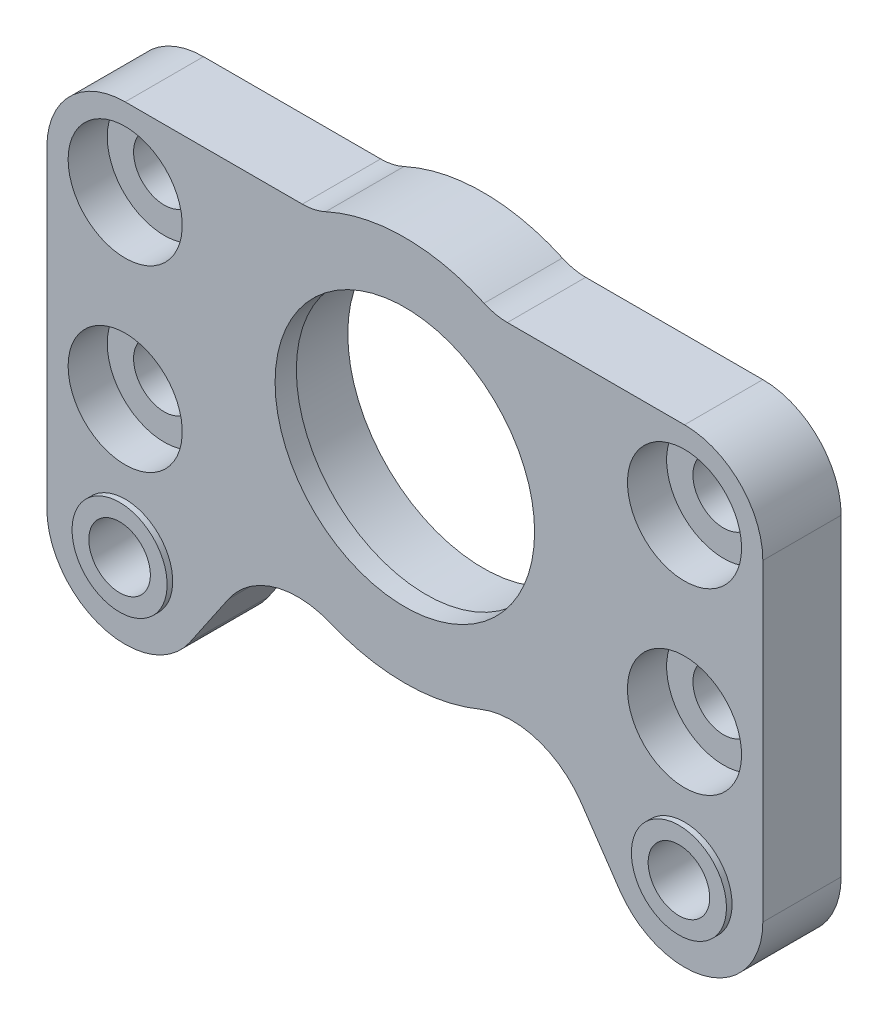
SolidWorks part; units mm, degrees
ref_plane "Front Plane" through (0, 0, 0) normal (0, 0, 1) x (1, 0, 0)
ref_plane "Top Plane" through (0, 0, 0) normal (0, 1, 0) x (1, 0, 0)
ref_plane "Right Plane" through (0, 0, 0) normal (1, 0, 0) x (0, 0, -1)
sketch "Sketch1" plane through (0, 0, 0) normal (0, 0, 1) x (1, 0, 0)
  line L4 (64, 35) -> (64, 7)
  line L7 (32, 27) -> (20.4, 27) construction
  line L8 (51.2137, 3.0607) -> (47.7667, 8.1237)
  line L10 (32, 44) -> (32, 38.6)
  line L11 (40, 42) -> (57, 42)
  line L12 (32, 15.4) -> (32, 9.5)
  line L13 (32, 38.6) -> (32, 15.4) construction
  line L14 (57, 35) -> (57, 7) construction
  arc A0 (32, 15.4) -> (32, 38.6) centre (32, 27) ccw
  arc A1 (40, 42) -> (32, 44) centre (32, 27) ccw
  arc A2 (32, 9.5) -> (38.697, 10.8321) centre (32, 27) ccw
  arc A3 (51.2137, 3.0607) -> (64, 7) centre (57, 7) ccw
  arc A4 (47.7667, 8.1237) -> (38.697, 10.8321) centre (41.5671, 3.903) ccw
  arc A5 (57, 42) -> (64, 35) centre (57, 35) cw
  dimension "D1" = 7
  dimension "D4" = 11.6
  dimension "D5" = 17
  dimension "D6" = 17.5
  dimension "D7" = 7.5
  dimension "D8" = 20
  dimension "D2" = 28
  dimension "D3" = 25
  dimension "D9" = 15
extrude "Boss-Extrude1" add sketch "Sketch1" along normal blind 7 separate body
sketch "Sketch3" plane through (0, 0, 7) normal (0, 0, 1) x (1, 0, 0)
  line L0 (57, 35) -> (57, 19) construction
  line L1 (57, 19) -> (57, 7) construction
  circle A0 centre (57, 35) radius 2.75
  circle A1 centre (57, 19) radius 2.75
  circle A2 centre (57, 7) radius 2.75
  dimension "D1" = 5.5
  dimension "D2" = 16
  dimension "D3" = 12
extrude "Cut-Extrude1" cut sketch "Sketch3" against normal through all both and the other way through all
sketch "Sketch4" plane through (0, 0, 0) normal (0, 0, -1) x (-1, 0, 0)
  circle A0 centre (-32, 27) radius 12.1
  dimension "D1" = 24.2
extrude "Cut-Extrude2" cut sketch "Sketch4" against normal blind 5.1
sketch "Sketch5" plane through (0, 0, 7) normal (0, 0, 1) x (1, 0, 0)
  circle A0 centre (57, 7) radius 2.75 construction
  circle A1 centre (57, 7) radius 2.75
  circle A2 centre (57, 7) radius 4.25
  dimension "D1" = 8.5
extrude "Boss-Extrude2" add sketch "Sketch5" along normal blind 0.5
sketch "Sketch6" plane through (0, 0, 7) normal (0, 0, 1) x (1, 0, 0)
  circle A0 centre (57, 19) radius 5.1
  circle A1 centre (57, 35) radius 5.1
  dimension "D1" = 10.2
extrude "Cut-Extrude3" cut sketch "Sketch6" against normal blind 3.5
fillet "Fillet1" radius 5 1 edges at (40, 42, 3.5)
sketch "Sketch8" plane through (0, 0, 0) normal (0, 0, -1) x (-1, 0, 0)
  line L1 (-54.5463, 11.25) -> (-59.4537, 11.25)
  line L2 (-59.4537, 11.25) -> (-61.9075, 7)
  line L3 (-61.9075, 7) -> (-59.4537, 2.75)
  line L4 (-59.4537, 2.75) -> (-54.5463, 2.75)
  line L5 (-54.5463, 2.75) -> (-52.0925, 7)
  line L6 (-52.0925, 7) -> (-54.5463, 11.25)
  circle A0 centre (-57, 7) radius 4.25 construction
  dimension "D1" = 8.5
extrude "Cut-Extrude4" cut sketch "Sketch8" against normal blind 3.5
mirror "Mirror2" about plane through (32, 44, 7) normal (1, 0, 0) of bodies 109 102
